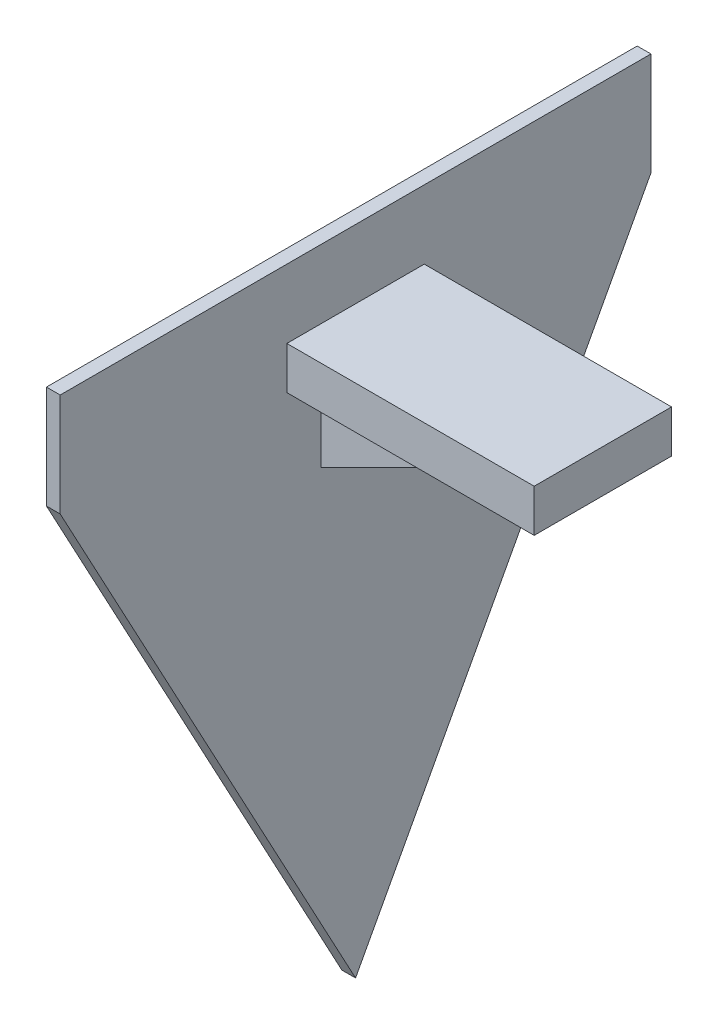
SolidWorks part; units mm, degrees
material "Acrylic (Medium-high impact)"
ref_plane "Front Plane" through (0, 0, 0) normal (0, 0, 1) x (1, 0, 0)
ref_plane "Top Plane" through (0, 0, 0) normal (0, 1, 0) x (1, 0, 0)
ref_plane "Right Plane" through (0, 0, 0) normal (1, 0, 0) x (0, 0, -1)
sketch "Sketch1" plane through (0, 0, 0) normal (1, 0, 0) x (0, 0, -1)
  line L0 (-43, 47.5) -> (43, 47.5)
  line L1 (43, 47.5) -> (43, 32.5)
  line L2 (43, 32.5) -> (0, -47.5)
  line L3 (0, -47.5) -> (-43, 32.5)
  line L4 (-43, 32.5) -> (-43, 47.5)
  line L5 (0, -47.5) -> (0, 47.5) construction
  point P2 (0, 0)
  dimension "D1" = 95
  dimension "D2" = 15
  dimension "D3" = 86
extrude "Boss-Extrude1" add sketch "Sketch1" along normal blind 2
sketch "Sketch2" plane through (2, 0, 0) normal (1, 0, 0) x (0, 0, -1)
  line L0 (43, 47.5) -> (-43, 47.5) construction
  line L1 (-10, 37.5) -> (10, 37.5)
  line L2 (-10, 37.5) -> (-10, 31.3)
  line L3 (-10, 31.3) -> (10, 31.3)
  line L4 (10, 37.5) -> (10, 31.3)
  line L5 (0, 47.5) -> (0, 37.5) construction
  line L6 (0, 37.5) -> (45.6875, 37.5) construction
  line L7 (0, -47.5) -> (43, 32.5) construction
  point P14 (0, 47.5)
  point P15 (0, 37.5)
  dimension "D1" = 6.2
  dimension "D2" = 20
  dimension "D3" = 10
extrude "Boss-Extrude2" add sketch "Sketch2" along normal blind 36
sketch "Sketch3" plane through (0, 0, 0) normal (0, 0, 1) x (1, 0, 0)
  line L0 (2, 19.3682) -> (25.8636, 31.3)
  line L1 (2, 32.5) -> (2, -47.5) construction
  line L2 (38, 31.3) -> (2, 31.3) construction
  line L3 (25.8636, 31.3) -> (12, 31.3)
  line L4 (12, 31.3) -> (2, 26.3)
  line L5 (2, 26.3) -> (2, 19.3682)
  dimension "D1" = 6.2
  dimension "D2" = 5
  dimension "D3" = 10
extrude "Boss-Extrude3" add sketch "Sketch3" along normal mid plane 10
